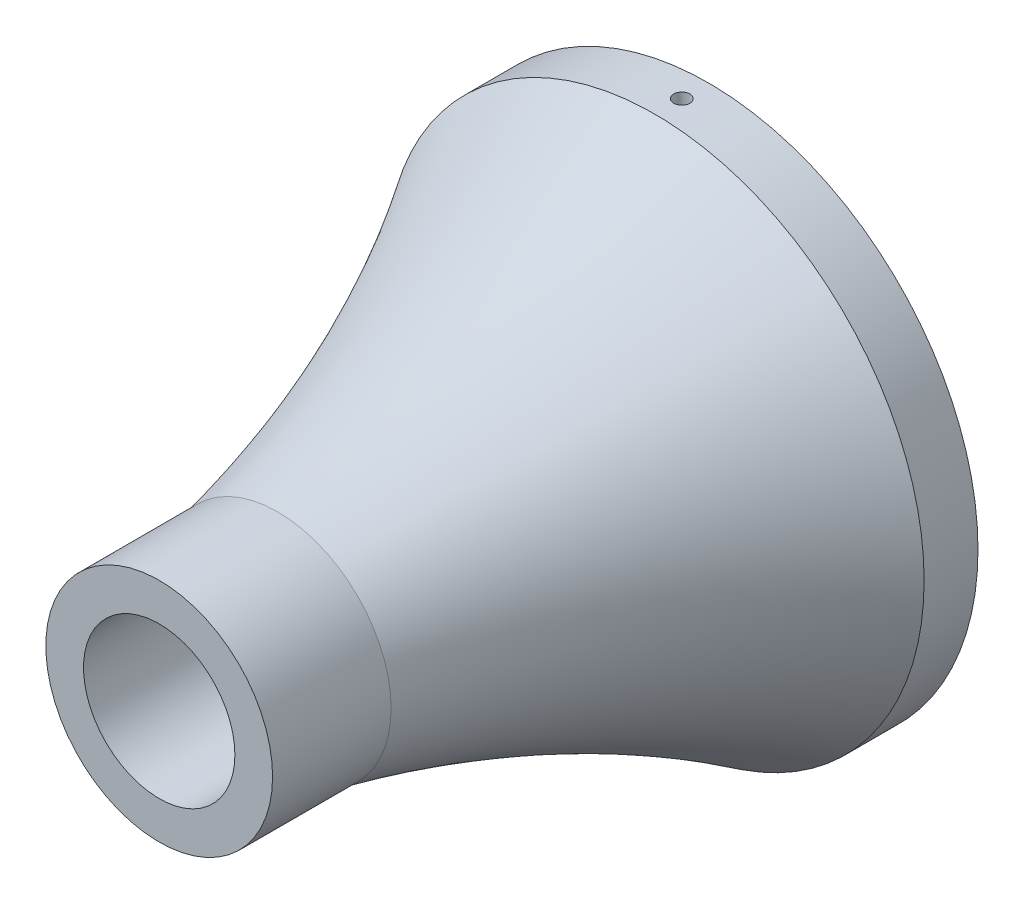
SolidWorks part; units mm, degrees
ref_plane "Front Plane" through (0, 0, 0) normal (0, 0, 1) x (1, 0, 0)
ref_plane "Top Plane" through (0, 0, 0) normal (0, 1, 0) x (1, 0, 0)
ref_plane "Right Plane" through (0, 0, 0) normal (1, 0, 0) x (0, 0, -1)
sketch "Sketch2" plane through (0, 0, 0) normal (0, 0, 1) x (1, 0, 0)
  circle A0 centre (0, 0) radius 25
  circle A1 centre (0, 0) radius 50
  dimension "D1" = 50
  dimension "D2" = 100
extrude "Boss-Extrude1" add sketch "Sketch2" along normal blind 10
sketch "Sketch3" plane through (0, 0, 0) normal (0, 1, 0) x (1, 0, 0)
  line L0 (50, 0) -> (-50, 0) construction
  line L1 (-50, -10) -> (50, -10) construction
  line L2 (50, 0) -> (-50, 0) construction
  line L3 (-50, -10) -> (50, -10) construction
  line L4 (-50, 0) -> (50, -10) construction
  circle A0 centre (0, -5) radius 1.5
  dimension "D1" = 3
extrude "Cut-Extrude1" cut sketch "Sketch3" against normal through all both and the other way through all
ref_plane "Motor-Start" through (0, 0, 30) normal (0, 0, 1) x (1, 0, 0)
sketch "Sketch5" plane through (0, 0, 30) normal (0, 0, 1) x (1, 0, 0)
  line L0 (-14.05, 14.05) -> (14.05, -14.05) construction
  line L1 (-14.05, 14.05) -> (14.05, 14.05)
  line L2 (-14.05, 14.05) -> (-14.05, -14.05)
  line L3 (-14.05, -14.05) -> (14.05, -14.05)
  line L4 (14.05, 14.05) -> (14.05, -14.05)
  line L5 (-21.05, 21.05) -> (-21.05, -21.05)
  line L6 (-21.05, -21.05) -> (21.05, -21.05)
  line L7 (21.05, 21.05) -> (21.05, -21.05)
  line L8 (-21.05, 21.05) -> (21.05, 21.05)
  dimension "D1" = 28.1
  dimension "D2" = 7
extrude "Boss-Extrude3" add sketch "Sketch5" along normal blind 32 separate body
sketch "Sketch6" plane through (0, 21.05, 0) normal (0, 1, 0) x (1, 0, 0)
  line L5 (21.05, -30) -> (-21.05, -30) construction
  line L6 (21.05, -30) -> (-21.05, -30) construction
  line L7 (-7.5, -32.5) -> (7.5, -32.5)
  line L8 (-7.5, -32.5) -> (-7.5, -42.5)
  line L9 (-7.5, -42.5) -> (7.5, -42.5)
  line L10 (7.5, -32.5) -> (7.5, -42.5)
  point P4 (0, -32.5)
  point P5 (0, -30)
  dimension "D1" = 10
  dimension "D2" = 15
  dimension "D3" = 2.5
extrude "Cut-Extrude2" cut sketch "Sketch6" against normal up to next (7 mm away)
sketch "Sketch7" plane through (0, 0, 62) normal (0, 0, 1) x (1, 0, 0)
  line L0 (14.05, -14.05) -> (14.05, 14.05) construction
  line L6 (21.05, 21.05) -> (-21.05, 21.05)
  line L7 (-21.05, 21.05) -> (-21.05, -21.05)
  line L8 (-21.05, -21.05) -> (21.05, -21.05)
  line L9 (21.05, -21.05) -> (21.05, 21.05)
  line L10 (21.05, 21.05) -> (-21.05, 21.05)
  line L11 (-21.05, 21.05) -> (-21.05, -21.05)
  line L12 (-21.05, -21.05) -> (21.05, -21.05)
  line L13 (21.05, -21.05) -> (21.05, 21.05)
  circle A0 centre (0, 0) radius 14.05
  dimension "D1" = 0
extrude "Boss-Extrude4" add sketch "Sketch7" along normal blind 40
sketch "Sketch11" plane through (0, 0, 102) normal (0, 0, 1) x (1, 0, 0)
  line L4 (21.05, -21.05) -> (21.05, 21.05)
  line L5 (21.05, 21.05) -> (-21.05, 21.05)
  line L6 (-21.05, 21.05) -> (-21.05, -21.05)
  line L7 (-21.05, -21.05) -> (21.05, -21.05)
  line L9 (0, 21.05) -> (-21.05, 21.05)
  line L10 (-21.05, 21.05) -> (-21.05, 0)
  arc A0 (0, 21.05) -> (-21.05, 0) centre (0, 0) ccw
  dimension "D1" = 0
extrude "Cut-Extrude3" cut sketch "Sketch11" against normal up to surface (72 mm away)
pattern_circular "CirPattern1" count 4 over 360 about axis through (0, 0, 102) along (0, 0, 1) of "Cut-Extrude3"
sketch "Sketch10" plane through (0, 0, 0) normal (0, 1, 0) x (1, 0, 0)
  line L0 (-50, -10) -> (50, -10) construction
  line L1 (-50, -10) -> (-25, -10)
  line L6 (0, 0) -> (0, -21.7399) construction
  line L8 (-21.05, -30) -> (-21.05, -80)
  line L9 (-21.05, -30) -> (-21.05, -102) construction
  spline S0 degree 2 poles (-25, -10) (-21.9247, -19.7903) (-21.05, -30) knots 0 0 0 1 1 1
  spline S1 degree 2 poles (-50, -10) (-29.0913, -42.247) (-21.05, -80) knots 0 0 0 1 1 1
  dimension "D1" = 50
revolve "Revolve2" add sketch "Sketch10" angle 360 about L6
sketch "Sketch12" plane through (0, 0, 30) normal (0, 0, -1) x (-1, 0, 0)
  line L0 (-14.05, 14.05) -> (14.05, 14.05) construction
  line L1 (14.05, 14.05) -> (14.05, -14.05) construction
  line L2 (14.05, -14.05) -> (-14.05, -14.05) construction
  line L3 (-14.05, -14.05) -> (-14.05, 14.05) construction
  line L4 (-10.05, -10.05) -> (-10.05, 10.05)
  line L5 (-10.05, 10.05) -> (10.05, 10.05)
  line L6 (10.05, 10.05) -> (10.05, -10.05)
  line L7 (10.05, -10.05) -> (-10.05, -10.05)
  circle A1 centre (0, 0) radius 21.05
  circle A2 centre (0, 0) radius 21.05
  dimension "D2" = 4
  dimension "D1" = 0
extrude "Boss-Extrude5" add sketch "Sketch12" along normal blind 10
